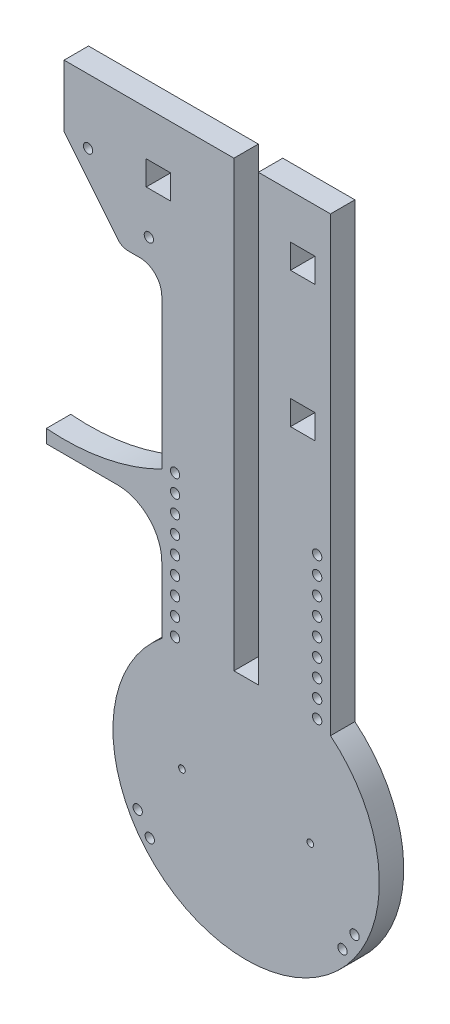
SolidWorks part; units mm, degrees
material "ﾁｰｸ材"
ref_plane "正面" through (0, 0, 0) normal (0, 0, 1) x (1, 0, 0)
ref_plane "平面" through (0, 0, 0) normal (0, 1, 0) x (1, 0, 0)
ref_plane "右側面" through (0, 0, 0) normal (1, 0, 0) x (0, 0, -1)
sketch "ｽｹｯﾁ1" plane through (0, 0, 0) normal (0, 0, 1) x (1, 0, 0)
  line L0 (19, 125) -> (-41, 125)
  line L1 (-19, 95) -> (-19, 56.2164)
  line L2 (19, 125) -> (19, 23.2164)
  line L6 (-28, 95) -> (-19, 95)
  line L7 (-41, 111) -> (-41, 125)
  line L8 (-28, 95) -> (-41, 111)
  line L9 (-45, 48.1635) -> (-19, 48.1635)
  line L10 (-45, 48.1635) -> (-45, 51.1635)
  line L11 (-19, 48.1635) -> (-19, 23.2164)
  arc A0 (-19, 23.2164) -> (19, 23.2164) centre (0, 0) ccw
  arc A1 (-45, 51.1635) -> (-19, 56.2164) centre (-41, 100) ccw
  dimension "D1" = 60
  dimension "D7" = 49
  dimension "D2" = 125
  dimension "D3" = 19
  dimension "D4" = 13
  dimension "D5" = 41
  dimension "D6" = 16
  dimension "D8" = 41
  dimension "D9" = 5
  dimension "D10" = 45
  dimension "D11" = 3
  dimension "D12" = 100
extrude "ﾎﾞｽ - 押し出し1" add sketch "ｽｹｯﾁ1" along normal blind 5.5
sketch "ｽｹｯﾁ3" plane through (0, 0, 5.5) normal (0, 0, 1) x (1, 0, 0)
  line L0 (0, 0) -> (0, 22.4882) construction
fillet "ﾌｨﾚｯﾄ2" radius 5 1 edges at (-19, 95, 2.75)
sketch "ｽｹｯﾁ5" plane through (0, 0, 5.5) normal (0, 0, 1) x (1, 0, 0)
  circle A0 centre (14.45, 0) radius 0.75
  circle A1 centre (-14.45, 0) radius 0.75
  dimension "D1" = 14.45
  dimension "D2" = 1.5
  dimension "D3" = 14.45
extrude "ｶｯﾄ - 押し出し3" cut sketch "ｽｹｯﾁ5" against normal through all
sketch "ｽｹｯﾁ6" plane through (0, 0, 5.5) normal (0, 0, 1) x (1, 0, 0)
  line L0 (0, 0) -> (-25.1601, -16.3392) construction
  line L1 (0, 0) -> (0, 22.4882) construction
  line L2 (-21.7018, -17.0742) -> (-24.425, -12.8809) construction
  line L3 (0, 0) -> (0, -5.9449) construction
  arc A0 (-19, 23.2164) -> (19, 23.2164) centre (0, 0) ccw construction
  circle A1 centre (-24.425, -12.8809) radius 1.05
  circle A2 centre (-21.7018, -17.0742) radius 1.05
  circle A3 centre (24.425, -12.8809) radius 1.05
  circle A4 centre (21.7018, -17.0742) radius 1.05
  point P12 (-23.0634, -14.9776)
  dimension "D2" = 5
  dimension "D3" = 2.1
  dimension "D4" = 2.1
  dimension "D1" = 123
  dimension "D5" = 27.5
extrude "ｶｯﾄ - 押し出し4" cut sketch "ｽｹｯﾁ6" against normal through all
sketch "ｽｹｯﾁ7" plane through (0, 0, 5.5) normal (0, 0, 1) x (1, 0, 0)
  line L0 (0, 0) -> (0, 22.4882) construction
  line L1 (-28, 95) -> (-24, 95) construction
  circle A0 centre (-21.9, 100) radius 1.05
  circle A1 centre (-35.6, 110.5) radius 1.05
  dimension "D1" = 2.1
  dimension "D3" = 13.7
  dimension "D5" = 5
  dimension "D2" = 21.9
  dimension "D4" = 10.5
extrude "ｶｯﾄ - 押し出し5" cut sketch "ｽｹｯﾁ7" against normal through all
fillet "ﾌｨﾚｯﾄ3" radius 3 1 edges at (-28, 95, 2.75)
fillet "ﾌｨﾚｯﾄ4" radius 10 1 edges at (-19, 48.1635, 2.75)
sketch "ｽｹｯﾁ8" plane through (0, 0, 5.5) normal (0, 0, 1) x (1, 0, 0)
  line L0 (0, 0) -> (0, 22.4882) construction
  line L1 (15.5, 109.5) -> (10, 109.5)
  line L2 (15.5, 109.5) -> (15.5, 115)
  line L3 (15.5, 115) -> (10, 115)
  line L4 (10, 109.5) -> (10, 115)
  line L5 (-22.5, 115) -> (-17, 115)
  line L6 (-22.5, 115) -> (-22.5, 109.5)
  line L7 (-22.5, 109.5) -> (-17, 109.5)
  line L8 (-17, 115) -> (-17, 109.5)
  line L9 (19, 125) -> (-41, 125) construction
  line L10 (15.5, 79) -> (10, 79)
  line L11 (15.5, 79) -> (15.5, 84.5)
  line L12 (15.5, 84.5) -> (10, 84.5)
  line L13 (10, 79) -> (10, 84.5)
  point P10 (-17, 112.25)
  dimension "D1" = 5.5
  dimension "D2" = 10
  dimension "D3" = 17
  dimension "D4" = 10
  dimension "D5" = 25
extrude "ｶｯﾄ - 押し出し6" cut sketch "ｽｹｯﾁ8" against normal through all
sketch "ｽｹｯﾁ9" plane through (0, 0, 5.5) normal (0, 0, 1) x (1, 0, 0)
  line L0 (0, 0) -> (0, 22.4882) construction
  line L1 (0, 0) -> (0, 13.9203) construction
  circle A0 centre (16, 25) radius 1.05
  circle A1 centre (16, 29) radius 1.05
  circle A2 centre (16, 33) radius 1.05
  circle A3 centre (16, 37) radius 1.05
  circle A4 centre (16, 41) radius 1.05
  circle A5 centre (16, 45) radius 1.05
  circle A6 centre (16, 49) radius 1.05
  circle A7 centre (16, 53) radius 1.05
  circle A8 centre (16, 57) radius 1.05
  circle A9 centre (-16, 57) radius 1.05
  circle A10 centre (-16, 53) radius 1.05
  circle A11 centre (-16, 49) radius 1.05
  circle A12 centre (-16, 45) radius 1.05
  circle A13 centre (-16, 41) radius 1.05
  circle A14 centre (-16, 37) radius 1.05
  circle A15 centre (-16, 33) radius 1.05
  circle A16 centre (-16, 29) radius 1.05
  circle A17 centre (-16, 25) radius 1.05
  dimension "D1" = 2.1
  dimension "D2" = 16
  dimension "D4" = 25
  dimension "D3" = 9
extrude "ｶｯﾄ - 押し出し7" cut sketch "ｽｹｯﾁ9" against normal through all
sketch "ｽｹｯﾁ10" plane through (0, 0, 5.5) normal (0, 0, 1) x (1, 0, 0)
  line L0 (19, 125) -> (-41, 125) construction
  line L1 (2.75, 25) -> (-2.75, 25)
  line L2 (2.75, 25) -> (2.75, 125)
  line L3 (2.75, 125) -> (-2.75, 125)
  line L4 (-2.75, 25) -> (-2.75, 125)
  line L5 (2.75, 25) -> (-2.75, 125) construction
  line L6 (2.75, 125) -> (-2.75, 25) construction
  point P0 (0, 75)
  dimension "D1" = 5.5
  dimension "D2" = 25
extrude "ｶｯﾄ - 押し出し8" cut sketch "ｽｹｯﾁ10" against normal through all
